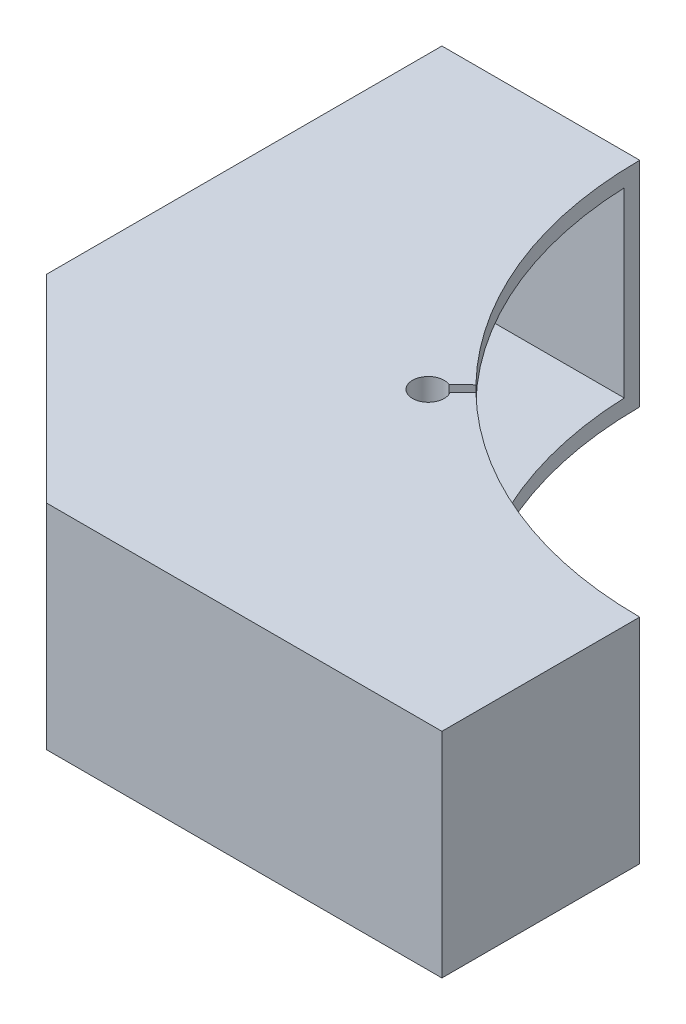
SolidWorks part; units mm, degrees
ref_plane "Front Plane" through (0, 0, 0) normal (0, 0, 1) x (1, 0, 0)
ref_plane "Top Plane" through (0, 0, 0) normal (0, 1, 0) x (1, 0, 0)
ref_plane "Right Plane" through (0, 0, 0) normal (1, 0, 0) x (0, 0, -1)
sketch "Sketch3" plane through (0, 0, 0) normal (0, 1, 0) x (1, 0, 0)
  line L0 (0, 0) -> (-50, 0)
  line L1 (0, 0) -> (0, 25)
  line L2 (-50, 0) -> (-75, 25)
  line L3 (-75, 25) -> (-75, 75)
  line L4 (-75, 75) -> (-50, 75)
  line L5 (-35.777, 40.0714) -> (-37.4897, 38.3994)
  line L6 (-34.9285, 39.2229) -> (-36.5766, 37.6139)
  arc A0 (-50, 75) -> (-35.777, 40.0714) centre (0, 75) ccw
  arc A1 (0, 25) -> (-34.9285, 39.2229) centre (0, 75) cw
  arc A2 (-36.5766, 37.6139) -> (-37.4897, 38.3994) centre (-38.277, 36.5609) cw
  dimension "D1" = 50
  dimension "D6" = 50
  dimension "D2" = 25
  dimension "D3" = 50
  dimension "D4" = 50
  dimension "D5" = 25
  dimension "D7" = 0
  dimension "D8" = 1.2
extrude "Boss-Extrude1" add sketch "Sketch3" along normal blind 27
shell "Shell1" thickness 2
sketch "Sketch5" plane through (-25, 0, 25) normal (-0.7071, 0, 0.7071) x (0.7071, 0, 0.7071)
  line L0 (-35.3553, 0) -> (-70.7107, 27)
  circle A0 centre (-53.033, 13.5) radius 12.7
extrude "Cut-Extrude1" cut sketch "Sketch5" against normal blind 9.525 contours L0 A0 | L0 A0
sketch "Sketch6" plane through (0, 2, 0) normal (0, 1, 0) x (1, 0, 0)
  line L0 (-34.7771, 39.0757) -> (-34.9285, 39.2229)
  line L2 (-36.5766, 37.6139) -> (-34.9285, 39.2229)
  line L3 (-37.4897, 38.3994) -> (-35.777, 40.0714)
  arc A0 (-35.777, 40.0714) -> (-34.7771, 39.0757) centre (-38.277, 36.5609) ccw
  arc A1 (-36.5766, 37.6139) -> (-37.4897, 38.3994) centre (-38.277, 36.5609) cw
  arc A3 (-37.4897, 38.3994) -> (-36.5766, 37.6139) centre (-38.277, 36.5609) ccw construction
  arc A4 (-34.9285, 39.2229) -> (-2, 25.04) centre (0, 75) ccw construction
extrude "Boss-Extrude2" add sketch "Sketch6" along normal blind 4
sketch "Sketch7" plane through (0, 25, 0) normal (0, -1, 0) x (1, 0, 0)
  line L0 (-36.5766, -37.6139) -> (-34.9285, -39.2229)
  line L1 (-37.4897, -38.3994) -> (-35.777, -40.0714)
  arc A0 (-36.5766, -37.6139) -> (-37.4897, -38.3994) centre (-38.277, -36.5609) ccw
  arc A1 (-36.5766, -37.6139) -> (-37.4897, -38.3994) centre (-38.277, -36.5609) ccw construction
  arc A2 (-34.9285, -39.2229) -> (-35.8003, -40.0487) centre (-38.277, -36.5609) ccw
  arc M9 (-37.4897, -38.3994) -> (-36.5766, -37.6139) centre (-38.277, -36.5609) cw
  line M10 (-36.5766, -37.6139) -> (-34.9285, -39.2229)
extrude "Boss-Extrude3" add sketch "Sketch7" along normal blind 4 contours A2 L1 M10 M9
